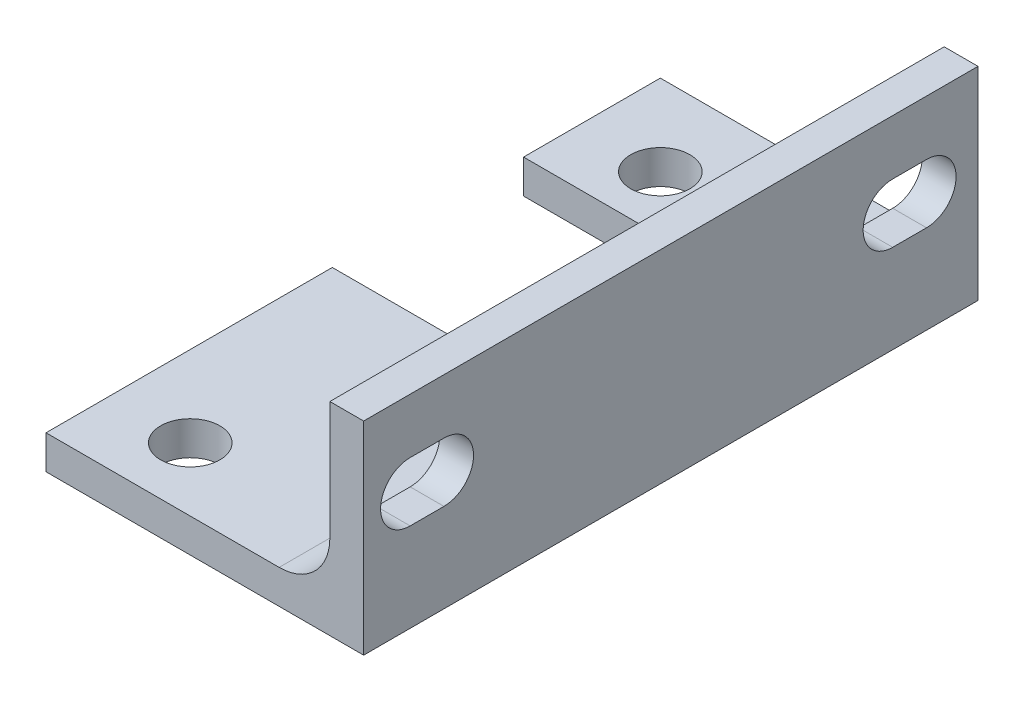
SolidWorks part; units mm, degrees
ref_plane "Front Plane" through (0, 0, 0) normal (0, 0, 1) x (1, 0, 0)
ref_plane "Top Plane" through (0, 0, 0) normal (0, 1, 0) x (1, 0, 0)
ref_plane "Right Plane" through (0, 0, 0) normal (1, 0, 0) x (0, 0, -1)
sketch "Sketch1" plane through (0, 0, 0) normal (0, 1, 0) x (1, 0, 0)
  line L0 (6.8692, 36.3687) -> (4.3704, 38.8698) construction
  line L5 (6.8536, 3.7687) -> (6.8692, 36.3687) construction
  line L6 (6.8536, 3.7687) -> (4.3524, 1.2699) construction
  line L7 (5.603, 2.5193) -> (16.8665, 2.5193)
  line L8 (6.8692, 36.3687) -> (4.3704, 38.8698) construction
  line L9 (6.8536, 3.7687) -> (6.8692, 36.3687) construction
  line L10 (6.8536, 3.7687) -> (4.3524, 1.2699) construction
  line L11 (4.3704, 38.8698) -> (16.8665, 38.8698)
  line L12 (5.603, 2.5193) -> (-1.9293, 2.5193)
  line L13 (-1.9293, 2.5193) -> (-1.9293, 19.4606)
  line L14 (-1.9293, 19.4606) -> (6.8665, 19.4606)
  line L15 (4.3704, 38.8698) -> (-1.9293, 38.8698)
  line L16 (-1.9293, 38.8698) -> (-1.9293, 30.7758)
  line L17 (-1.9293, 30.7758) -> (6.8665, 30.7758)
  line L21 (16.8665, 38.8698) -> (16.8665, 2.5193)
  line L22 (6.8665, 30.7758) -> (6.8665, 19.4606)
  circle A4 centre (2.8681, 34.0706) radius 1.75
  circle A5 centre (2.8548, 6.2706) radius 1.75
  dimension "D1" = 3.5
  dimension "D2" = 3.5
  dimension "D3" = 10
extrude "Boss-Extrude1" add sketch "Sketch1" along normal blind 2
sketch "Sketch4" plane through (0, 2, 0) normal (0, 1, 0) x (1, 0, 0)
  line L0 (-1.9293, 2.5193) -> (16.8665, 2.5193) construction
  line L1 (16.8665, 38.8698) -> (14.8665, 38.8698)
  line L2 (16.8665, 38.8698) -> (16.8665, 2.5193)
  line L3 (16.8665, 2.5193) -> (14.8665, 2.5193)
  line L4 (14.8665, 38.8698) -> (14.8665, 2.5193)
  dimension "D1" = 2
extrude "Boss-Extrude3" add sketch "Sketch4" along normal blind 10
sketch "Sketch5" plane through (14.8665, 0, 0) normal (-1, 0, 0) x (0, 0, 1)
  line L0 (-38.8698, 7) -> (-2.5193, 7) construction
  line L1 (-38.8698, 12) -> (-38.8698, 2) construction
  line L2 (-2.5193, 12) -> (-2.5193, 2) construction
  line L3 (-34.8228, 2) -> (-34.8228, 12) construction
  line L4 (-38.8698, 2) -> (-30.7758, 2) construction
  line L5 (-38.8698, 12) -> (-2.5193, 12) construction
  line L6 (-8.0206, 2) -> (-4.5206, 0) construction
  line L7 (-6.2706, 1) -> (-6.2706, 7) construction
  line L8 (-5.2706, 7) -> (-7.2706, 7) construction
  line L9 (-5.2706, 5.25) -> (-7.2706, 5.25)
  line L10 (-5.2706, 8.75) -> (-7.2706, 8.75)
  line L11 (-33.8228, 7) -> (-35.8228, 7) construction
  line L12 (-33.8228, 5.25) -> (-35.8228, 5.25)
  line L13 (-33.8228, 8.75) -> (-35.8228, 8.75)
  arc A2 (-5.2706, 5.25) -> (-5.2706, 8.75) centre (-5.2706, 7) ccw
  arc A3 (-7.2706, 8.75) -> (-7.2706, 5.25) centre (-7.2706, 7) ccw
  arc A4 (-33.8228, 5.25) -> (-33.8228, 8.75) centre (-33.8228, 7) ccw
  arc A5 (-35.8228, 8.75) -> (-35.8228, 5.25) centre (-35.8228, 7) ccw
  point P20 (-34.8228, 7)
  point P23 (-6.2706, 7)
  dimension "D1" = 3.5
  dimension "D2" = 2
  dimension "D3" = 3.5
  dimension "D4" = 2
extrude "Cut-Extrude1" cut sketch "Sketch5" against normal blind 10
fillet "Fillet1" radius 3 1 edges at (14.8665, 2, -20.6946)
